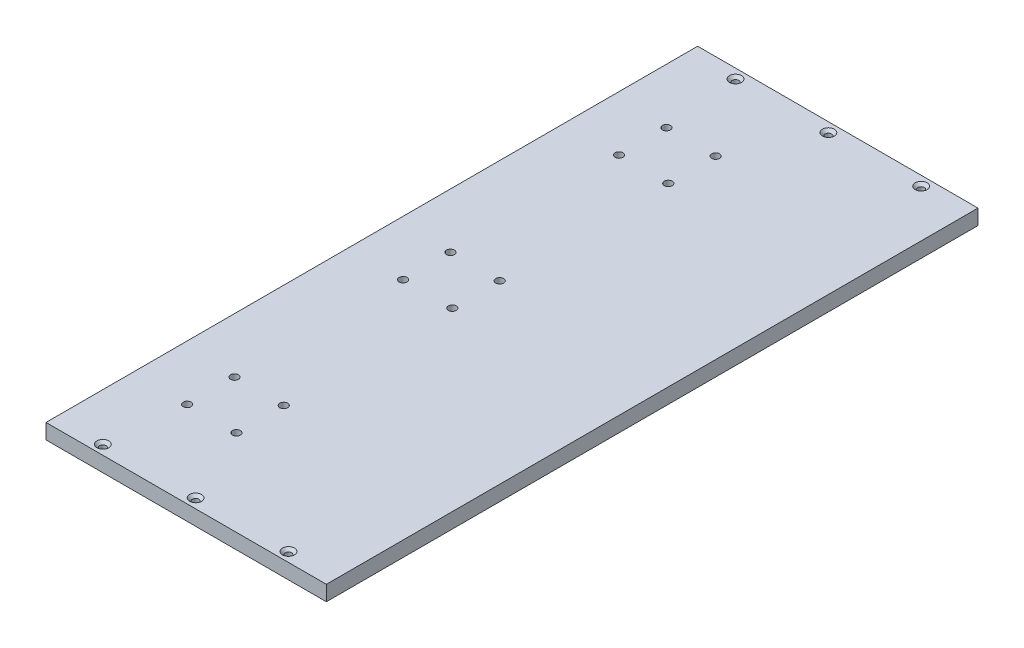
SolidWorks part; units mm, degrees
ref_plane "Front Plane" through (0, 0, 0) normal (0, 0, 1) x (1, 0, 0)
ref_plane "Top Plane" through (0, 0, 0) normal (0, 1, 0) x (1, 0, 0)
ref_plane "Right Plane" through (0, 0, 0) normal (1, 0, 0) x (0, 0, -1)
sketch "Sketch1" plane through (0, 0, 0) normal (0, 1, 0) x (1, 0, 0)
  line L1 (-74, -172) -> (74, -172)
  line L2 (-74, -172) -> (-74, 172)
  line L3 (-74, 172) -> (74, 172)
  line L4 (74, -172) -> (74, 172)
  line L5 (-74, -172) -> (74, 172) construction
  line L6 (-74, 172) -> (74, -172) construction
  point P0 (0, 0)
  dimension "D1" = 344
  dimension "D2" = 148
extrude "Boss-Extrude1" add sketch "Sketch1" along normal blind 8
sketch "Sketch2" plane through (0, 8, 0) normal (0, 1, 0) x (1, 0, 0)
  line L0 (74, -167) -> (-74, -167) construction
  line L1 (74, -172) -> (74, 172) construction
  line L2 (-74, 172) -> (-74, -172) construction
  line L3 (-74, -172) -> (74, -172) construction
  point P8 (0, -167)
  point P9 (-49, -167)
  point P10 (49, -167)
  dimension "D1" = 5
  dimension "D2" = 49
  dimension "D3" = 49
hole_wizard "CSK for M3 Countersunk Flat Head1" positions "3DSketch1" profile "Sketch3" countersink size "M3" standard "BSI"
sketch3d "3DSketch1"
  point P0 (-49, 8, 167)
  point P3 (0, 8, 167)
  point P6 (49, 8, 167)
sketch "Sketch3" plane through (-49, 8, 167) normal (1, 0, 0) x (0, 0, 1)
  line L0 (0, 0) -> (0, 16.0215)
  line L1 (0, 16.0215) -> (1.7, 15)
  line L2 (1.7, 15) -> (1.7, 1.45)
  line L3 (1.7, 1.45) -> (3.15, 0)
  line L5 (3.15, 0) -> (0, 0)
  line L6 (-1.7, 1.45) -> (-3.15, 0) construction
  line L10 (0, 16.0215) -> (-1.7, 15) construction
  line L11 (0, -6.35) -> (0, 107.95) construction
  dimension "Hole Dia." = 3.4
  dimension "Hole Depth" = 15
  dimension "Near C'Sink Dia." = 6.3
  dimension "Near C'Sink Angle" = 90
  dimension "Drill Angle" = 118
mirror "Mirror1" about plane through (0, 0, 0) normal (0, 0, 1) of "CSK for M3 Countersunk Flat Head1"
sketch "Sketch4" plane through (0, 8, 0) normal (0, 1, 0) x (1, 0, 0)
  line L0 (-81, 0) -> (-45, 0) construction
  line L1 (-45, -12.5) -> (-45, 12.5) construction
  line L2 (-74, 172) -> (-74, -172) construction
  line L3 (-45, 12.5) -> (-19, 12.5) construction
  line L4 (-45, -12.5) -> (-19, -12.5) construction
  dimension "D1" = 36
  dimension "D2" = 26
  dimension "D3" = 26
  dimension "D4" = 25
  dimension "D5" = 7
hole_wizard "M5x0.8 Tapped Hole1" positions "3DSketch2" profile "Sketch5" tap size "M5x0.8" standard "BSI" end condition through all
sketch3d "3DSketch2"
  point P0 (-19, 8, -12.5)
  point P3 (-45, 8, -12.5)
  point P6 (-45, 8, 12.5)
  point P9 (-19, 8, 12.5)
sketch "Sketch5" plane through (-19, 8, -12.5) normal (1, 0, 0) x (0, 0, 1)
  line L0 (0, 0) -> (0, 8)
  line L1 (0, 8) -> (2.1, 8)
  line L2 (2.1, 8) -> (2.1, 0)
  line L5 (2.1, 0) -> (0, 0)
  line L11 (0, -6.35) -> (0, 107.95) construction
  dimension "Thru Tap Drill Dia." = 4.2
  dimension "Thru Tap Drill Depth" = 8
cosmetic thread "Hole Thread1" parameters "D2"=5
cosmetic thread "Hole Thread2" parameters "D2"=5
cosmetic thread "Hole Thread3" parameters "D2"=5
cosmetic thread "Hole Thread4" parameters "D2"=5
pattern_linear "LPattern1" count 2 spacing 114 along (0, 0, 1) count 2 spacing 114 along (0, 0, -1) of "M5x0.8 Tapped Hole1"
